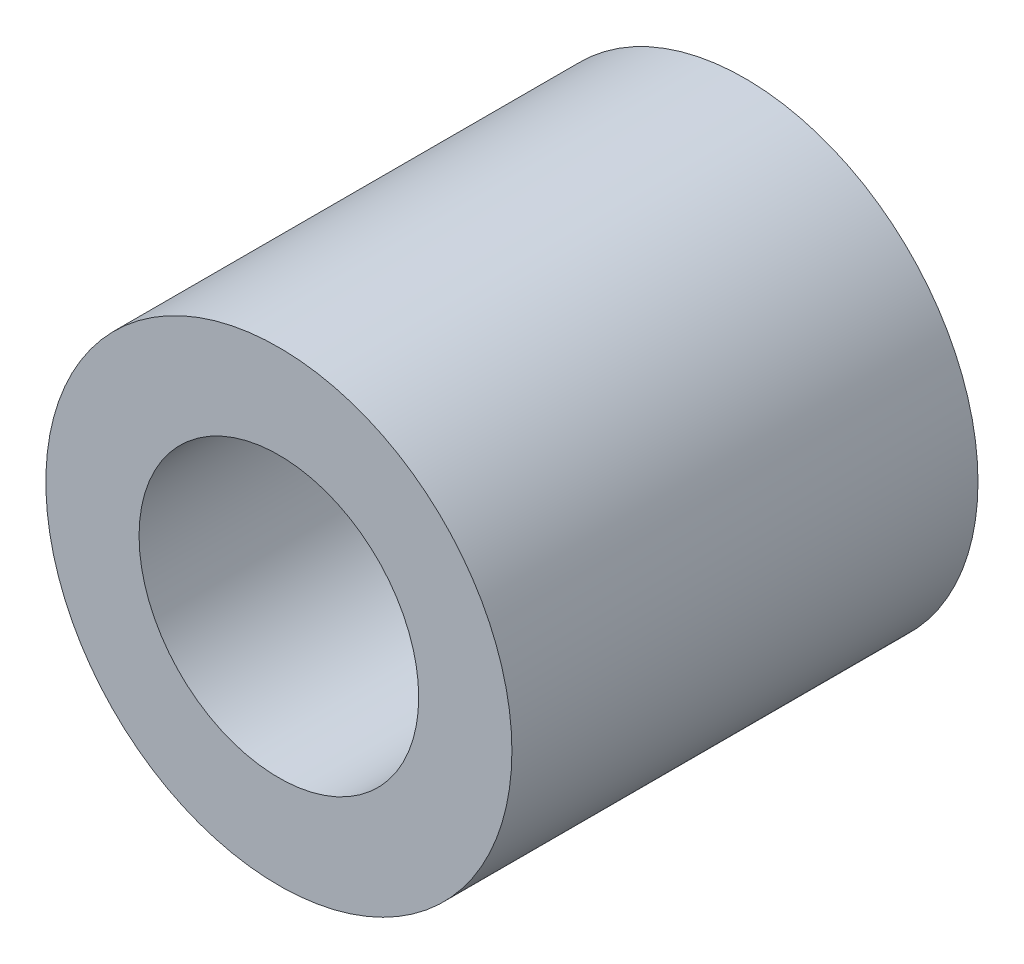
SolidWorks part; units mm, degrees
ref_plane "前视基准面" through (0, 0, 0) normal (0, 0, 1) x (1, 0, 0)
ref_plane "上视基准面" through (0, 0, 0) normal (0, 1, 0) x (1, 0, 0)
ref_plane "右视基准面" through (0, 0, 0) normal (1, 0, 0) x (0, 0, -1)
sketch "草图1" plane through (0, 0, 0) normal (0, 0, 1) x (1, 0, 0)
  line L1 (22.776, 0) -> (-21.5401, 0) construction
  line L2 (0, -20.1567) -> (0, 24.2386) construction
  circle A0 centre (0, 0) radius 1.5
  circle A1 centre (0, 0) radius 2.5
  dimension "D1" = 3
  dimension "D2" = 5
extrude "凸台-拉伸1" add sketch "草图1" along normal blind 5
